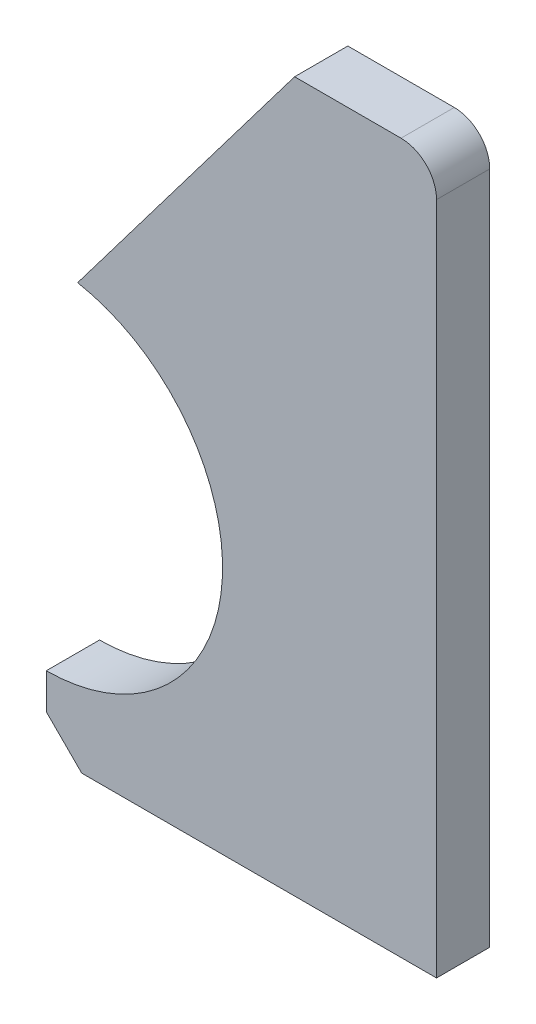
SolidWorks part; units mm, degrees
ref_plane "Front Plane" through (0, 0, 0) normal (0, 0, 1) x (1, 0, 0)
ref_plane "Top Plane" through (0, 0, 0) normal (0, 1, 0) x (1, 0, 0)
ref_plane "Right Plane" through (0, 0, 0) normal (1, 0, 0) x (0, 0, -1)
sketch "Sketch1" plane through (0, 0, 0) normal (0, 0, 1) x (1, 0, 0)
  line L0 (0, 0) -> (100, 0)
  line L1 (100, 0) -> (100, 190)
  line L2 (90, 200) -> (60, 200)
  line L3 (-10, 10) -> (0, 0)
  line L4 (-1.1494, 119.1538) -> (60, 200)
  line L5 (-10, 10) -> (-10, 20)
  arc A0 (-10, 20) -> (-1.1494, 119.1538) centre (-10.304, 69.9991) ccw
  arc A1 (90, 200) -> (100, 190) centre (90, 190) cw
  point P11 (100, 200)
  dimension "D4" = 50
  dimension "D5" = 10
  dimension "D1" = 200
  dimension "D2" = 40
  dimension "D3" = 100
  dimension "D6" = 10
extrude "Boss-Extrude1" add sketch "Sketch1" along normal blind 15
